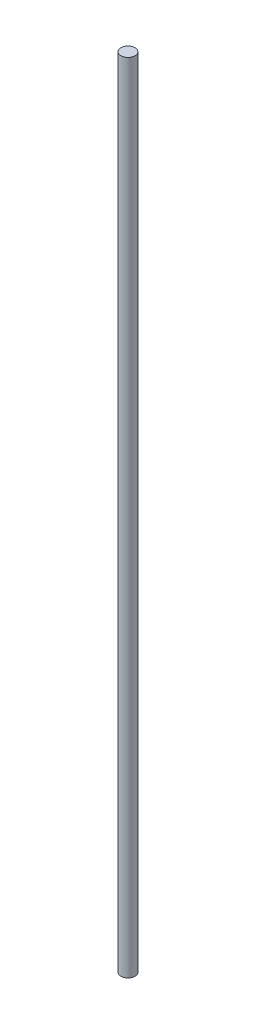
SolidWorks part; units mm, degrees
ref_plane "Front Plane" through (0, 0, 0) normal (0, 0, 1) x (1, 0, 0)
ref_plane "Top Plane" through (0, 0, 0) normal (0, 1, 0) x (1, 0, 0)
ref_plane "Right Plane" through (0, 0, 0) normal (1, 0, 0) x (0, 0, -1)
sketch "Sketch1" plane through (0, 0, 0) normal (0, 1, 0) x (1, 0, 0)
  circle A0 centre (0, 0) radius 4
  dimension "D1" = 8
extrude "Boss-Extrude1" add sketch "Sketch1" along normal blind 454.9
equation "\"d\"= 8"
equation "\"l\" = 454.9"
equation "\"D1@Boss-Extrude1\"=\"l\""
equation "\"D1@Sketch1\"=\"d\""
